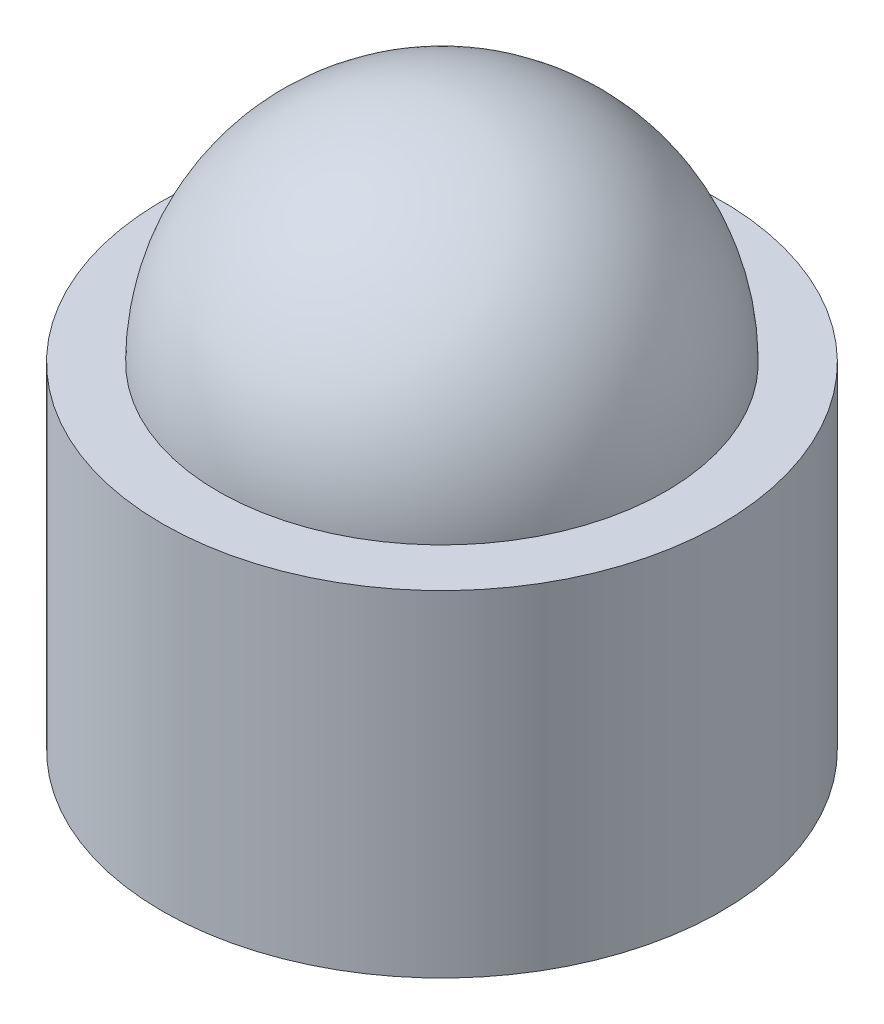
SolidWorks part; units mm, degrees
ref_plane "Front Plane" through (0, 0, 0) normal (0, 0, 1) x (1, 0, 0)
ref_plane "Top Plane" through (0, 0, 0) normal (0, 1, 0) x (1, 0, 0)
ref_plane "Right Plane" through (0, 0, 0) normal (1, 0, 0) x (0, 0, -1)
sketch "Sketch1" plane through (0, 0, 0) normal (0, 1, 0) x (1, 0, 0)
  circle A0 centre (0, 0) radius 25
extrude "Boss-Extrude4" add sketch "Sketch1" along normal blind 30
sketch "Sketch3" plane through (0, 30, 0) normal (0, 1, 0) x (1, 0, 0)
  line L0 (-9.6577, 17.5137) -> (9.6577, -17.5137)
  arc A0 (9.6577, -17.5137) -> (-9.6577, 17.5137) centre (0, 0) ccw
revolve "Revolve1" add sketch "Sketch3" angle 180 about L0
